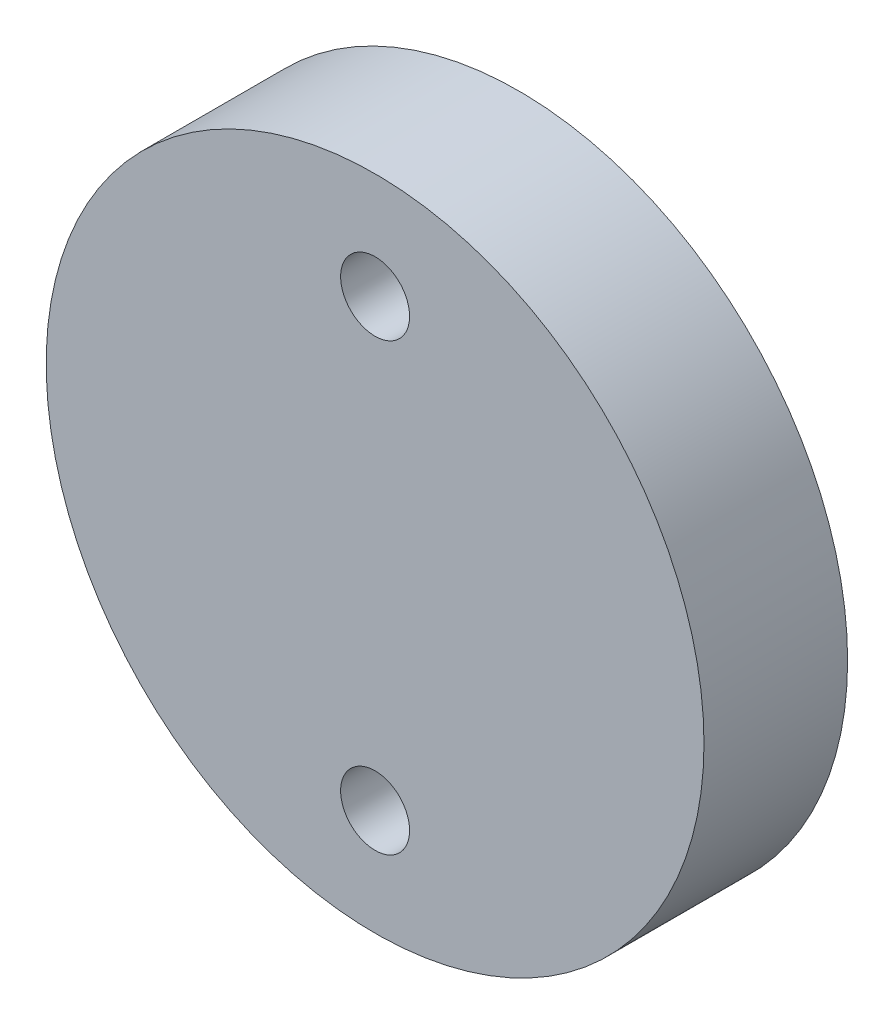
SolidWorks part; units mm, degrees
ref_plane "Front Plane" through (0, 0, 0) normal (0, 0, 1) x (1, 0, 0)
ref_plane "Top Plane" through (0, 0, 0) normal (0, 1, 0) x (1, 0, 0)
ref_plane "Right Plane" through (0, 0, 0) normal (1, 0, 0) x (0, 0, -1)
sketch "Sketch1" plane through (0, 0, 0) normal (0, 0, 1) x (1, 0, 0)
  line L0 (0, 7.75) -> (0, -7.75) construction
  circle A0 centre (0, 0) radius 11.45
  circle A1 centre (0, 7.75) radius 1.2
  circle A2 centre (0, -7.75) radius 1.2
  dimension "D1" = 22.9
  dimension "D2" = 2.4
  dimension "D3" = 15.5
extrude "Boss-Extrude1" add sketch "Sketch1" along normal blind 5
